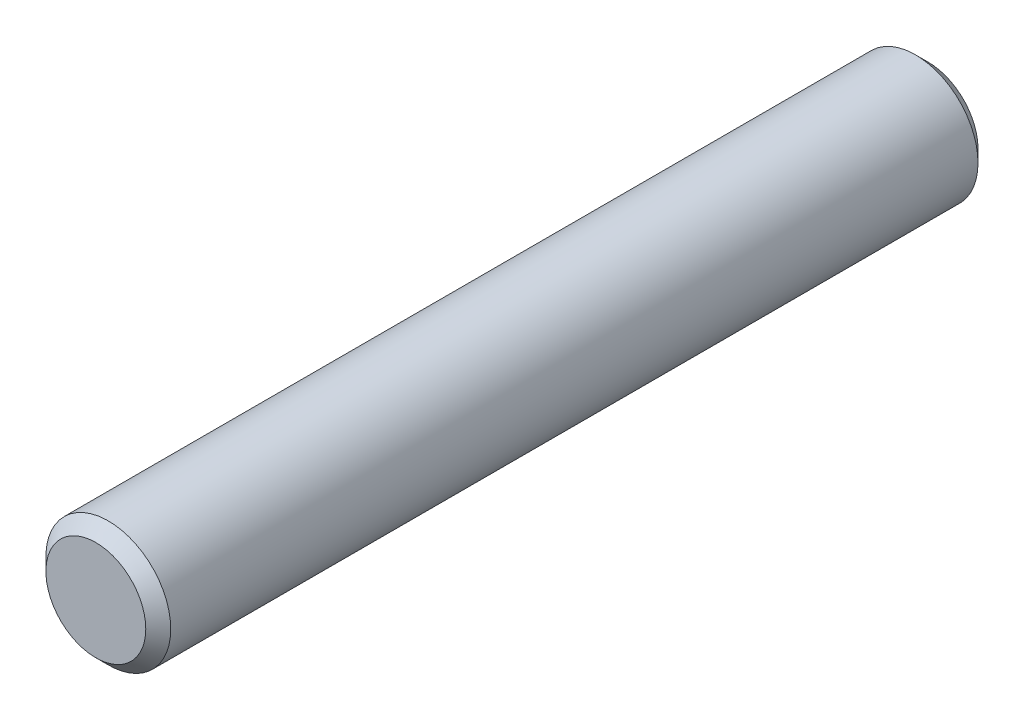
SolidWorks part; units mm, degrees
ref_plane "Front Plane" through (0, 0, 0) normal (0, 0, 1) x (1, 0, 0)
ref_plane "Top Plane" through (0, 0, 0) normal (0, 1, 0) x (1, 0, 0)
ref_plane "Right Plane" through (0, 0, 0) normal (1, 0, 0) x (0, 0, -1)
sketch "Sketch1" plane through (0, 0, 0) normal (0, 0, 1) x (1, 0, 0)
  circle A0 centre (0, 0) radius 1.5
  dimension "D1" = 3
extrude "Boss-Extrude1" add sketch "Sketch1" along normal mid plane 20
chamfer "Chamfer1" distance 0.3 angle 45 2 edges at (1.5, 0, 10) (1.5, 0, -10)
